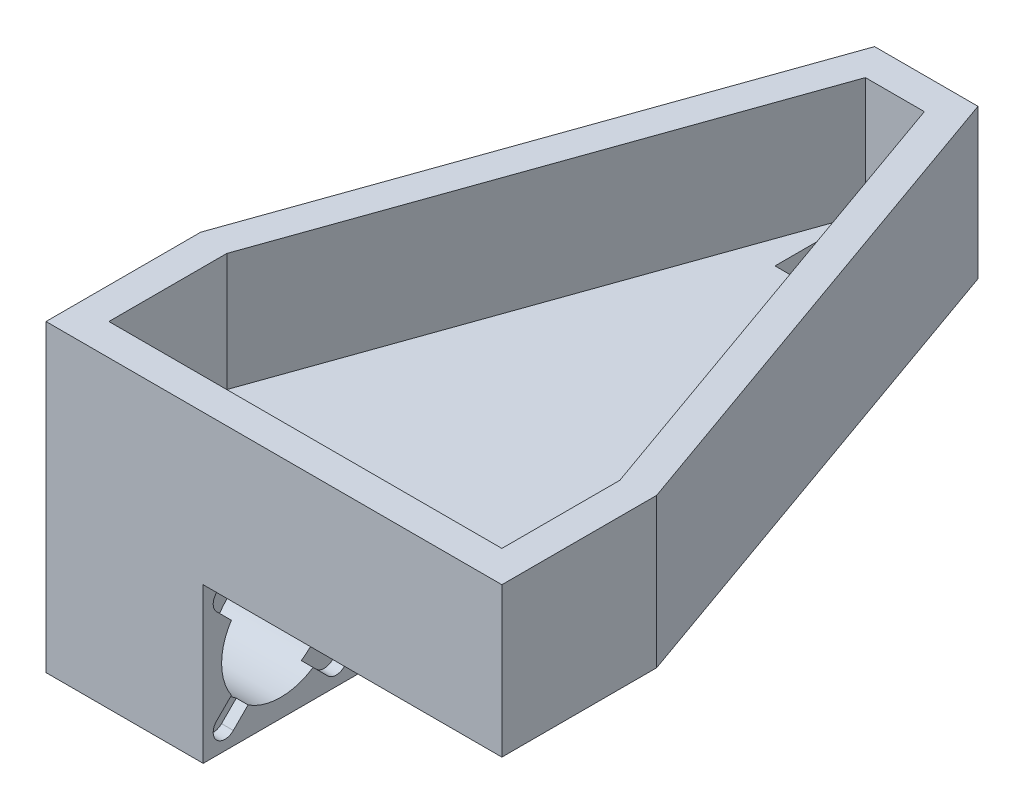
SolidWorks part; units mm, degrees
ref_plane "Front Plane" through (0, 0, 0) normal (0, 0, 1) x (1, 0, 0)
ref_plane "Top Plane" through (0, 0, 0) normal (0, 1, 0) x (1, 0, 0)
ref_plane "Right Plane" through (0, 0, 0) normal (1, 0, 0) x (0, 0, -1)
sketch "Sketch1" plane through (0, 0, 0) normal (0, 1, 0) x (1, 0, 0)
  line L8 (-50, 0) -> (50, 0)
  line L9 (50, 0) -> (50, 30)
  line L10 (50, 30) -> (7.5, 150)
  line L11 (7.5, 150) -> (-7.5, 150)
  line L12 (0, 160.8838) -> (0, -18.8522) construction
  line L13 (-50, 30) -> (-7.5, 150)
  line L14 (-50, 0) -> (-50, 30)
  point P14 (0, 150)
  point P16 (0, 0)
  dimension "D1" = 30
  dimension "D2" = 7.5
  dimension "D3" = 150
  dimension "D4" = 100
extrude "Boss-Extrude1" add sketch "Sketch1" along normal blind 30
shell "Shell2" thickness 8
sketch "Sketch2" plane through (0, -8, 0) normal (0, -1, 0) x (-1, 0, 0)
  line L0 (7.5, 150) -> (-7.5, 150)
  line L1 (7.5, 150) -> (7.5, 127)
  line L2 (-7.5, 150) -> (-7.5, 127)
  line L3 (7.5, 127) -> (-7.5, 127)
  line L4 (7.5, 150) -> (50, 30) construction
  line L5 (7.5, 150) -> (50, 30) construction
  dimension "D1" = 23
extrude "Cut-Extrude1" cut sketch "Sketch2" against normal up to surface (8 mm away) up to face at (0, 0, -60)
sketch "Sketch3" plane through (0, 0, -150) normal (0, 0, 1) x (1, 0, 0)
  line L0 (-7.5, 0) -> (7.5, 0) construction
  line L1 (7.5, 0) -> (7.5, -8) construction
  line L2 (-7.5, 0) -> (7.5, 0)
  line L3 (-7.5, 0) -> (-7.5, 3)
  line L4 (7.5, 0) -> (7.5, 3)
  line L5 (-7.5, 3) -> (7.5, 3)
  dimension "D1" = 3
extrude "Cut-Extrude2" cut sketch "Sketch3" against normal blind 5
sketch "Sketch4" plane through (-58, 0, 0) normal (-1, 0, 0) x (0, 0, 1)
  line L5 (-31.3748, -47.3748) -> (8, -47.3748)
  line L6 (-31.3748, -47.3748) -> (-31.3748, -8)
  line L7 (-31.3748, -8) -> (8, -8)
  line L8 (8, -47.3748) -> (8, -8)
  line L9 (-31.3748, -47.3748) -> (8, -8) construction
  line L10 (-31.3748, -8) -> (8, -47.3748) construction
  circle A0 centre (-11.6874, -27.6874) radius 15
  point P0 (-11.6874, -27.6874)
  dimension "D1" = 30
extrude "Boss-Extrude2" add sketch "Sketch4" against normal blind 40
sketch "Sketch5" plane through (-18, 0, 0) normal (1, 0, 0) x (0, 0, -1)
  line L0 (11.6874, -27.6874) -> (31.3748, -8) construction
  line L2 (27.9509, -15.6666) -> (24.201, -19.4164)
  line L3 (23.7082, -11.424) -> (19.9584, -15.1738)
  arc A0 (27.9509, -15.6666) -> (23.7082, -11.424) centre (25.8295, -13.5453) ccw
  arc A2 (24.201, -19.4164) -> (19.9584, -15.1738) centre (11.6874, -27.6874) ccw
  circle A8 centre (11.6874, -27.6874) radius 15 construction
  dimension "D1" = 3
  dimension "D2" = 20
extrude "Cut-Extrude3" cut sketch "Sketch5" against normal blind 3
pattern_circular "CirPattern1" count 4 over 360 about axis through (0, -27.6874, -11.6874) along (1, 0, 0) of "Cut-Extrude3"
